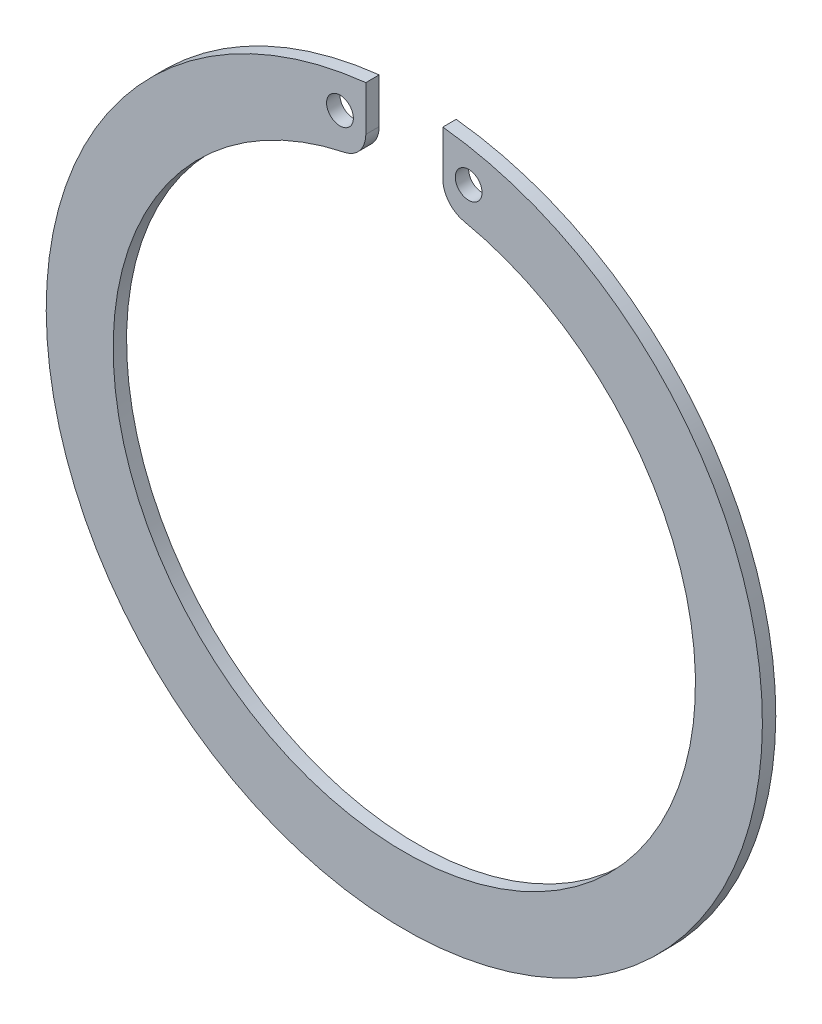
SolidWorks part; units mm, degrees
ref_plane "前视基准面" through (0, 0, 0) normal (0, 0, 1) x (1, 0, 0)
ref_plane "上视基准面" through (0, 0, 0) normal (0, 1, 0) x (1, 0, 0)
ref_plane "右视基准面" through (0, 0, 0) normal (1, 0, 0) x (0, 0, -1)
other "Configuration Table"
sketch "草图1" plane through (0, 0, 0) normal (0, 0, 1) x (1, 0, 0)
  circle A0 centre (0, 0) radius 21.75
  dimension "D1" = 43.5
extrude "拉伸-薄壁1" add sketch "草图1" along normal blind 1 thin
sketch "草图2" plane through (0, 0, 1) normal (0, 0, 1) x (1, 0, 0)
  line L0 (-2.8756, 7.6204) -> (2.8756, 7.6204)
  line L2 (2.8756, 7.6204) -> (2.8756, 28.3249)
  line L3 (2.8756, 28.3249) -> (-2.8756, 28.3249)
  line L4 (-2.8756, 7.6204) -> (-2.8756, 28.3249)
  line L6 (2.8756, 28.3249) -> (0.7736, 7.6204) construction
  line L7 (-0.7736, 7.6204) -> (-2.8756, 28.3249) construction
  point P0 (0, 0)
extrude "切除-拉伸1" cut sketch "草图2" against normal blind 10
fillet "圆角1" radius 2 2 edges at (2.8756, 21.5591, 0.5) (-2.8756, 21.5591, 0.5)
sketch "草图3" plane through (0, 0, 1) normal (0, 0, 1) x (1, 0, 0)
  line L0 (0, 0) -> (0, 29.6759) construction
  circle A0 centre (-4.8071, 23.8233) radius 1
  circle A1 centre (4.8071, 23.8233) radius 1
  dimension "D1" = 2
extrude "切除-拉伸2" cut sketch "草图3" against normal blind 10
